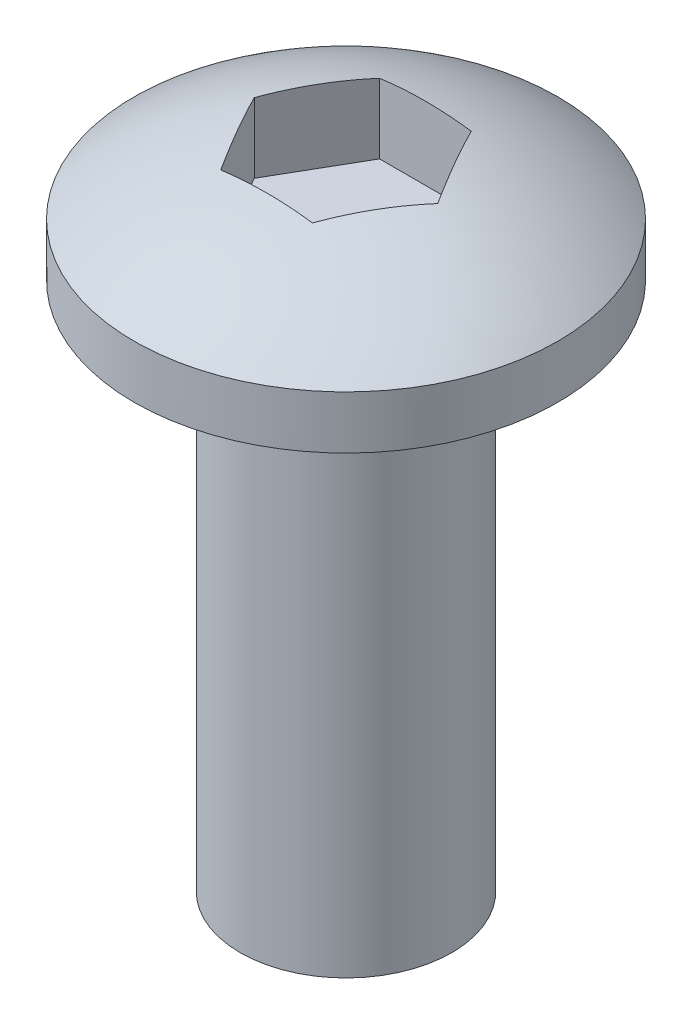
SolidWorks part; units mm, degrees
material "1.0570 (S355J2G3)"
ref_plane "Front Plane" through (0, 0, 0) normal (0, 0, 1) x (1, 0, 0)
ref_plane "Top Plane" through (0, 0, 0) normal (0, 1, 0) x (1, 0, 0)
ref_plane "Right Plane" through (0, 0, 0) normal (1, 0, 0) x (0, 0, -1)
sketch "Sketch1" plane through (0, 0, 0) normal (0, 1, 0) x (1, 0, 0)
  circle A0 centre (0, 0) radius 1
  dimension "D1" = 2
extrude "Boss-Extrude1" add sketch "Sketch1" along normal blind 5
sketch "Sketch2" plane through (0, 0, 0) normal (0, 0, 1) x (1, 0, 0)
  line L0 (0, 5) -> (-2, 5)
  line L1 (1, 5) -> (-1, 5) construction
  line L2 (0, 5) -> (0, 6.1751)
  line L3 (-2, 5) -> (-2, 5.5)
  arc A0 (0, 6.1751) -> (-2, 5.5) centre (0, 2.8751) ccw
  point P8 (0, 5.9776)
  point P9 (0, 0)
  dimension "D2" = 3.3
  dimension "D1" = 0.5
  dimension "D3" = 2
revolve "Revolve2" add sketch "Sketch2" angle 360 about L2
sketch "Sketch3" plane through (0, 0, 0) normal (0, 1, 0) x (1, 0, 0)
  line L1 (0.433, -0.75) -> (0.866, 0)
  line L2 (0.866, 0) -> (0.433, 0.75)
  line L3 (0.433, 0.75) -> (-0.433, 0.75)
  line L4 (-0.433, 0.75) -> (-0.866, 0)
  line L5 (-0.866, 0) -> (-0.433, -0.75)
  line L6 (-0.433, -0.75) -> (0.433, -0.75)
  circle A0 centre (0, 0) radius 0.75 construction
  dimension "D1" = 1.5
extrude "Cut-Extrude1" cut sketch "Sketch3" against normal blind 1.1 from offset 6.5
